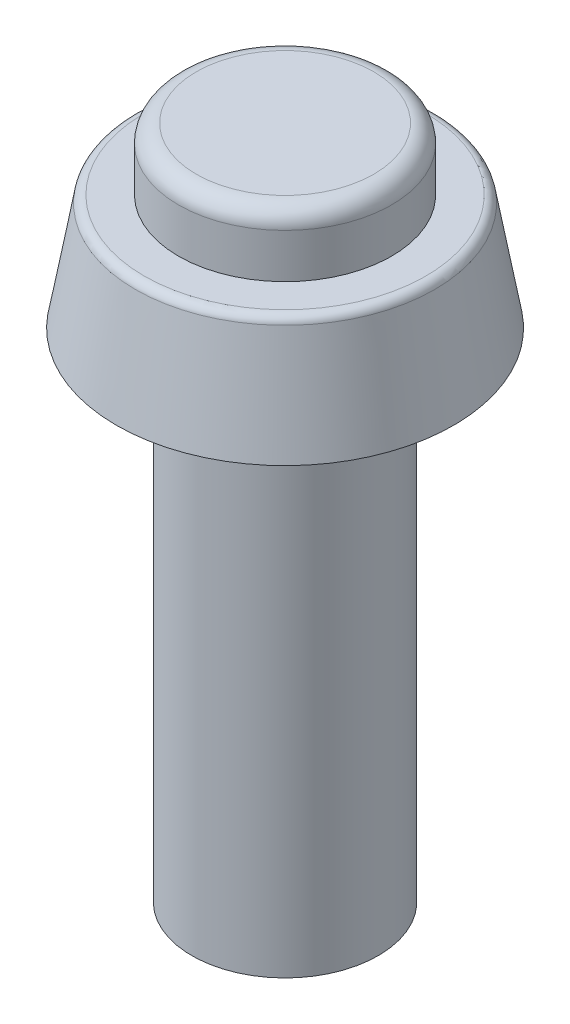
SolidWorks part; units mm, degrees
ref_plane "Front Plane" through (0, 0, 0) normal (0, 0, 1) x (1, 0, 0)
ref_plane "Top Plane" through (0, 0, 0) normal (0, 1, 0) x (1, 0, 0)
ref_plane "Right Plane" through (0, 0, 0) normal (1, 0, 0) x (0, 0, -1)
sketch "Sketch1" plane through (0, 0, 0) normal (0, 1, 0) x (1, 0, 0)
  circle A0 centre (0, 0) radius 9.5
  dimension "D1" = 19
extrude "Boss-Extrude1" add sketch "Sketch1" along normal blind 6.5 draft 10
sketch "Sketch2" plane through (0, 6.5, 0) normal (0, 1, 0) x (1, 0, 0)
  circle A0 centre (0, 0) radius 6
  dimension "D1" = 12
extrude "Boss-Extrude2" add sketch "Sketch2" along normal blind 3.5 separate body
sketch "Sketch3" plane through (0, 0, 0) normal (0, -1, 0) x (1, 0, 0)
  circle A0 centre (0, 0) radius 5.25
  dimension "D1" = 10.5
extrude "Boss-Extrude3" add sketch "Sketch3" along normal blind 28
fillet "Fillet1" radius 1 1 edges at (0, 10, 6)
fillet "Fillet2" radius 0.5 1 edges at (0, 6.5, 8.3539)
